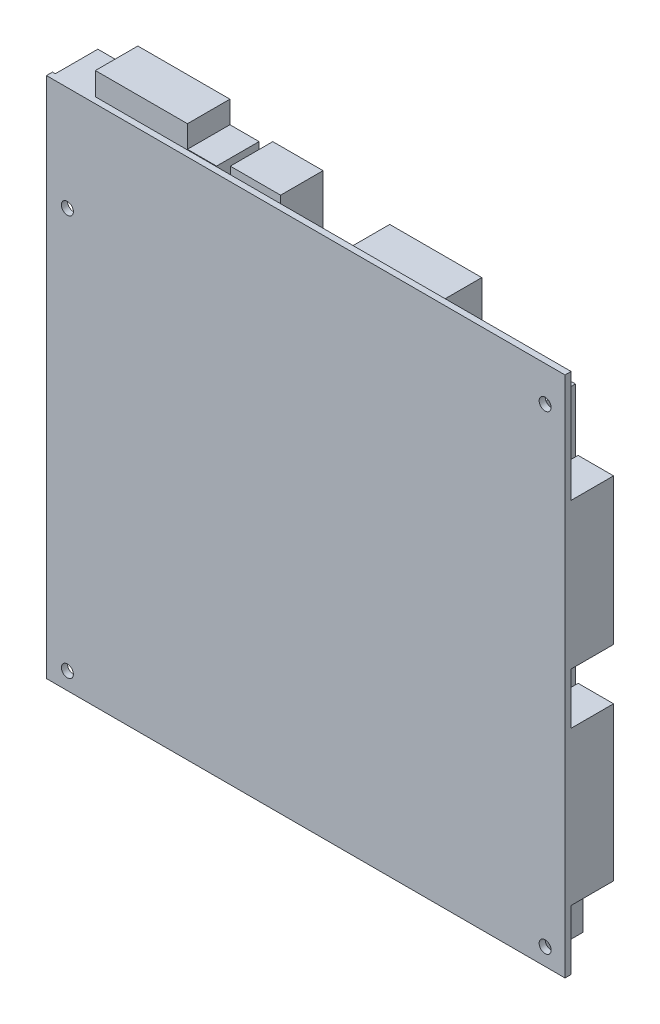
SolidWorks part; units mm, degrees
ref_plane "前视基准面" through (0, 0, 0) normal (0, 0, 1) x (1, 0, 0)
ref_plane "上视基准面" through (0, 0, 0) normal (0, 1, 0) x (1, 0, 0)
ref_plane "右视基准面" through (0, 0, 0) normal (1, 0, 0) x (0, 0, -1)
sketch "草图1" plane through (0, 0, 0) normal (0, 0, 1) x (1, 0, 0)
  line L1 (-164.3857, 166.5167) -> (6.5568, 166.5167)
  line L2 (-164.3857, 166.5167) -> (-164.3857, -5.6468)
  line L3 (-164.3857, -5.6468) -> (6.5568, -5.6468)
  line L4 (6.5568, 166.5167) -> (6.5568, -5.6468)
  arc A8 (-159.455, 0) -> (-155.505, 0) centre (-157.48, 0) ccw
  arc A9 (-155.505, 0) -> (-159.455, 0) centre (-157.48, 0) ccw
  arc A10 (-1.975, 0) -> (1.975, 0) centre (0, 0) ccw
  arc A11 (1.975, 0) -> (-1.975, 0) centre (0, 0) ccw
  arc A12 (-1.975, 154.92) -> (1.975, 154.92) centre (0, 154.92) ccw
  arc A13 (1.975, 154.92) -> (-1.975, 154.92) centre (0, 154.92) ccw
  arc A14 (-159.455, 132.08) -> (-155.505, 132.08) centre (-157.48, 132.08) ccw
  arc A15 (-155.505, 132.08) -> (-159.455, 132.08) centre (-157.48, 132.08) ccw
  point P5 (0, 0)
extrude "凸台-拉伸1" add sketch "草图1" against normal blind 2
sketch "草图2" plane through (0, 0, -2) normal (0, 0, -1) x (-1, 0, 0)
  line L1 (25, 130.679) -> (75, 130.679)
  line L2 (25, 130.679) -> (25, 43.679)
  line L3 (25, 43.679) -> (75, 43.679)
  line L4 (75, 130.679) -> (75, 43.679)
extrude "凸台-拉伸2" add sketch "草图2" along normal blind 35
sketch "草图3" plane through (0, 0, -2) normal (0, 0, -1) x (-1, 0, 0)
  line L0 (164.3857, 166.5167) -> (164.3857, -5.6468) construction
  line L1 (36.8765, 164.598) -> (67.2275, 164.598)
  line L2 (36.8765, 164.598) -> (36.8765, 133.026)
  line L3 (36.8765, 133.026) -> (67.2275, 133.026)
  line L4 (67.2275, 164.598) -> (67.2275, 133.026)
  line L5 (89.2059, 168.9588) -> (105.7768, 168.9588)
  line L6 (89.2059, 168.9588) -> (89.2059, 148.812)
  line L7 (89.2059, 148.812) -> (105.7768, 148.812)
  line L8 (105.7768, 168.9588) -> (105.7768, 148.812)
  line L9 (119.9058, 174.0173) -> (150.2568, 174.0173)
  line L10 (119.9058, 174.0173) -> (119.9058, 153.26)
  line L11 (119.9058, 153.26) -> (150.2568, 153.26)
  line L12 (150.2568, 174.0173) -> (150.2568, 153.26)
  line L13 (77.6934, 74.5915) -> (164.3857, 74.5915)
  line L14 (77.6934, 74.5915) -> (77.6934, 50.52)
  line L15 (77.6934, 50.52) -> (164.3857, 50.52)
  line L16 (164.3857, 74.5915) -> (164.3857, 50.52)
  line L17 (164.3857, -5.6468) -> (-6.5568, -5.6468) construction
  line L18 (154.4431, 48.4268) -> (164.3857, 48.4268)
  line L19 (154.4431, 48.4268) -> (154.4431, 5.1679)
  line L20 (154.4431, 5.1679) -> (164.3857, 5.1679)
  line L21 (164.3857, 48.4268) -> (164.3857, 5.1679)
  line L22 (144.1517, -5.6468) -> (84.3218, -5.6468)
  line L23 (144.1517, -5.6468) -> (144.1517, 8.1332)
  line L24 (144.1517, 8.1332) -> (84.3218, 8.1332)
  line L25 (84.3218, -5.6468) -> (84.3218, 8.1332)
  line L26 (-6.5568, -5.6468) -> (-6.5568, 166.5167) construction
  line L27 (-6.5568, 64.6489) -> (5.13, 64.6489)
  line L28 (-6.5568, 64.6489) -> (-6.5568, 14.0639)
  line L29 (-6.5568, 14.0639) -> (5.13, 14.0639)
  line L30 (5.13, 64.6489) -> (5.13, 14.0639)
  line L31 (5.13, 81.5688) -> (-6.5568, 81.5688)
  line L32 (5.13, 81.5688) -> (5.13, 129.7118)
  line L33 (5.13, 129.7118) -> (-6.5568, 129.7118)
  line L34 (-6.5568, 81.5688) -> (-6.5568, 129.7118)
  line L36 (5.9826, 21.4704) -> (40.7661, 21.4704)
  line L37 (5.9826, 21.4704) -> (5.9826, 10.8672)
  line L38 (5.9826, 10.8672) -> (40.7661, 10.8672)
  line L39 (40.7661, 21.4704) -> (40.7661, 10.8672)
  line L40 (3.5257, 7.2466) -> (59.5157, 7.2466)
  line L41 (3.5257, 7.2466) -> (3.5257, -5.6468)
  line L42 (3.5257, -5.6468) -> (59.5157, -5.6468)
  line L43 (59.5157, 7.2466) -> (59.5157, -5.6468)
  line L44 (163.4451, 151.5876) -> (150.2568, 151.5876)
  line L45 (163.4451, 151.5876) -> (163.4451, 166.7165)
  line L46 (163.4451, 166.7165) -> (150.2568, 166.7165)
  line L47 (150.2568, 151.5876) -> (150.2568, 166.7165)
  line L48 (110.3, 160.2511) -> (119.9058, 160.2511)
  line L49 (110.3, 160.2511) -> (110.3, 166.7165)
  line L50 (110.3, 166.7165) -> (119.9058, 166.7165)
  line L51 (119.9058, 160.2511) -> (119.9058, 166.7165)
  line M2 (164.3857, -5.6468) -> (164.3857, 166.5167)
  line M3 (164.3857, 166.5167) -> (-6.5568, 166.5167)
  line M4 (-6.5568, 166.5167) -> (-6.5568, -5.6468)
  line M5 (-6.5568, -5.6468) -> (164.3857, -5.6468)
extrude "凸台-拉伸3" add sketch "草图3" along normal blind 14 contours L4 L1 L2 L3 | L8 L6 L7 M3 | L12 L10 L11 M3 | L8 L5 L6 M3 | L12 L9 L10 M3 | L47 L44 L45 L12 M3 | L14 L15 L13 M2 | L19 L20 L18 M2 | L25 L23 L24 M5 | L43 L40 L41 M5 | L39 L36 L37 L38 | L32 L33 L31 M4 | L30 L27 L29 M4 | L48 L51 L50 L49
chamfer "倒角1" distance 2 angle 45 4 edges at (-50, 130.679, -37) (-25, 87.179, -37) (-50, 43.679, -37) (-75, 87.179, -37)
